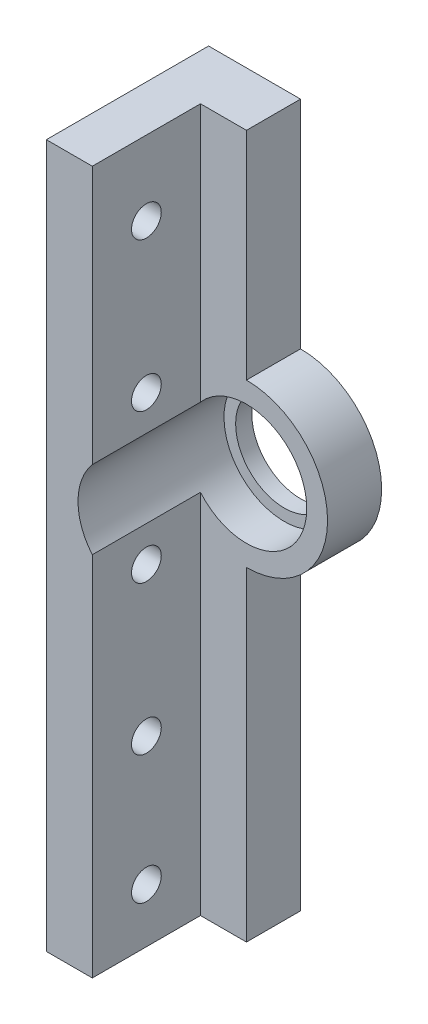
SolidWorks part; units mm, degrees
ref_plane "Front Plane" through (0, 0, 0) normal (0, 0, 1) x (1, 0, 0)
ref_plane "Top Plane" through (0, 0, 0) normal (0, 1, 0) x (1, 0, 0)
ref_plane "Right Plane" through (0, 0, 0) normal (1, 0, 0) x (0, 0, -1)
sketch "Sketch4" plane through (0, 0, -7) normal (0, 0, -1) x (-1, 0, 0)
  line L5 (0, 55) -> (0, 15)
  line L6 (17, 55) -> (0, 55)
  line L7 (17, -75) -> (17, 55)
  line L8 (0, -75) -> (17, -75)
  line L9 (0, -15) -> (0, -75)
  line L10 (0, 55) -> (0, 15)
  line L11 (17, 55) -> (0, 55)
  line L12 (17, -75) -> (17, 55)
  line L14 (0, -15) -> (0, -75)
  line L20 (0, -75) -> (17, -75)
  circle A0 centre (0, 0) radius 9 construction
  arc A1 (0, 15) -> (0, -15) centre (0, 0) ccw
  arc A2 (0, 15) -> (0, -15) centre (0, 0) ccw
  circle A3 centre (0, 0) radius 9
  dimension "D1" = 0
extrude "Boss-Extrude1" add sketch "Sketch4" along normal blind 3
sketch "Sketch5" plane through (0, 0, -7) normal (0, 0, 1) x (1, 0, 0)
  line L2 (0, -11.15) -> (0, -15)
  line L3 (0, 11.15) -> (0, 55)
  line L4 (-7, 55) -> (-7, 8.6789)
  line L5 (0, 55) -> (-7, 55)
  line L6 (0, 11.15) -> (0, 55)
  line L7 (-7, 55) -> (-7, 8.6789)
  line L8 (0, 55) -> (-7, 55)
  line L9 (0, 15) -> (0, 11.15)
  line L10 (0, -11.15) -> (0, -15)
  line L11 (0, 15) -> (0, 11.15)
  line L13 (0, -75) -> (0, -11.15)
  line L14 (-7, -75) -> (0, -75)
  line L15 (-7, -8.6789) -> (-7, -75)
  line L16 (0, -75) -> (0, -11.15)
  line L18 (-7, -8.6789) -> (-7, -75)
  line L21 (0, -55) -> (0, -15)
  line L22 (-17, -55) -> (0, -55)
  line L23 (-17, 55) -> (-17, -55)
  line L24 (0, 55) -> (-17, 55)
  line L25 (0, 15) -> (0, 55)
  line L26 (0, -55) -> (0, -15)
  line L27 (-17, -55) -> (0, -55)
  line L28 (-17, 55) -> (-17, -55)
  line L29 (0, 55) -> (-17, 55)
  line L30 (0, 15) -> (0, 55)
  line L37 (-7, -75) -> (0, -75)
  circle A0 centre (0, 0) radius 11.15
  arc A1 (0, 11.15) -> (-7, 8.6789) centre (0, 0) ccw
  arc A2 (0, 11.15) -> (-7, 8.6789) centre (0, 0) ccw
  arc A3 (-7, -8.6789) -> (0, -11.15) centre (0, 0) ccw
  arc A4 (0, -11.15) -> (0, 11.15) centre (0, 0) ccw
  arc A5 (0, -15) -> (0, 15) centre (0, 0) ccw
  arc A6 (0, -11.15) -> (0, 11.15) centre (0, 0) ccw
  arc A7 (0, -15) -> (0, 15) centre (0, 0) ccw
  arc A8 (-7, -8.6789) -> (0, -11.15) centre (0, 0) ccw
  arc A9 (0, -15) -> (0, 15) centre (0, 0) ccw
  arc A10 (0, -15) -> (0, 15) centre (0, 0) ccw
  dimension "D1" = 0
  dimension "D2" = 0
  dimension "D3" = 0
  dimension "D4" = 0
extrude "Boss-Extrude3" add sketch "Sketch5" along normal blind 7
sketch "Sketch6" plane through (0, 0, 0) normal (0, 0, 1) x (1, 0, 0)
  line L0 (0, 15) -> (0, -15)
  line L1 (-8.5, 55) -> (-8.5, 15)
  line L2 (0, 55) -> (-17, 55) construction
  line L3 (-8.5, 15) -> (0, 15)
  line L4 (0, -15) -> (-8.5, -15)
  line L5 (-8.5, -15) -> (-8.5, -55)
  line L7 (-8.5, 15) -> (-8.5, -16.0739)
  line L12 (0, 15) -> (0, 55)
  line L13 (0, 55) -> (-17, 55)
  line L14 (-17, 55) -> (-17, -55)
  line L15 (-17, -55) -> (0, -55)
  line L16 (0, -55) -> (0, -15)
  line L17 (0, 15) -> (0, 55)
  line L18 (0, 55) -> (-17, 55)
  line L19 (-17, 55) -> (-17, -55)
  line L21 (0, -55) -> (0, -15)
  line L23 (-17, -55) -> (0, -55)
  circle A0 centre (0, 0) radius 11.15
  arc A1 (0, -15) -> (0, 15) centre (0, 0) ccw construction
  arc A3 (0, -15) -> (0, 15) centre (0, 0) ccw
  arc A4 (0, -15) -> (0, 15) centre (0, 0) ccw
  dimension "D1" = 0
extrude "Boss-Extrude4" add sketch "Sketch6" along normal blind 10
sketch "Sketch7" plane through (0, 0, 10) normal (0, 0, 1) x (1, 0, 0)
  line L5 (-8.5, 7.2161) -> (-8.5, 55)
  line L6 (-8.5, 55) -> (-17, 55)
  line L7 (-17, 55) -> (-17, -55)
  line L8 (-17, -55) -> (-8.5, -55)
  line L9 (-8.5, -55) -> (-8.5, -7.2161)
  line L10 (-8.5, 7.2161) -> (-8.5, 55)
  line L11 (-8.5, 55) -> (-17, 55)
  line L12 (-17, 55) -> (-17, -55)
  line L14 (-8.5, -55) -> (-8.5, -7.2161)
  line L15 (-17, -55) -> (-8.5, -55)
  arc A1 (-8.5, 7.2161) -> (-8.5, -7.2161) centre (0, 0) ccw
  arc A2 (-8.5, 7.2161) -> (-8.5, -7.2161) centre (0, 0) ccw
  dimension "D1" = 0
extrude "Boss-Extrude5" add sketch "Sketch7" along normal blind 10
sketch "Sketch8" plane through (-8.5, 0, 0) normal (1, 0, 0) x (0, 0, -1)
  line L0 (-20, 0) -> (0, 0)
  line L3 (-20, 7.2161) -> (-20, -7.2161) construction
  line L4 (-10, 55) -> (-10, 27.5)
  line L5 (-20, 55) -> (0, 55) construction
  line L6 (-10, 27.5) -> (0, 27.5)
  line L7 (0, 15) -> (0, 55) construction
  circle A0 centre (-10, 41.25) radius 2.75
  circle A1 centre (-10, 13.75) radius 2.75
  circle A2 centre (-10, -13.75) radius 2.75
  circle A3 centre (-10, -41.25) radius 2.75
  dimension "D1" = 5.5
extrude "Cut-Extrude2" cut sketch "Sketch8" against normal blind 10 contours L4 A0 | A1 | L4 A0 | A2 | A3
sketch "Sketch10" plane through (0, 0, -7) normal (0, 0, 1) x (1, 0, 0)
  line L4 (0, -55) -> (-17, -55)
  line L5 (-17, -55) -> (-17, -75)
  line L6 (-17, -75) -> (0, -75)
  line L7 (0, -75) -> (0, -55)
  line L8 (0, -55) -> (-17, -55)
  line L9 (-17, -55) -> (-17, -75)
  line L10 (-17, -75) -> (0, -75)
  line L11 (0, -75) -> (0, -55)
  dimension "D1" = 0
extrude "Boss-Extrude7" add sketch "Sketch10" along normal up to surface (7 mm away) up to face at (0.0813, 0, 0)
sketch "Sketch11" plane through (0, -55, 0) normal (0, -1, 0) x (1, 0, 0)
  line L4 (-17, 20) -> (-17, 0)
  line L5 (-17, 0) -> (-8.5, 0)
  line L6 (-8.5, 0) -> (-8.5, 20)
  line L7 (-8.5, 20) -> (-17, 20)
  line L8 (-17, 20) -> (-17, 0)
  line L9 (-17, 0) -> (-8.5, 0)
  line L10 (-8.5, 0) -> (-8.5, 20)
  line L11 (-8.5, 20) -> (-17, 20)
  dimension "D1" = 0
extrude "Boss-Extrude8" add sketch "Sketch11" along normal up to surface (20 mm away) up to face at (-8.5, -75, -5)
sketch "Sketch12" plane through (-8.5, 0, 0) normal (1, 0, 0) x (0, 0, -1)
  line L0 (-10, -65) -> (-10, -75)
  line L1 (-20, -75) -> (0, -75) construction
  circle A0 centre (-10, -65) radius 2.75
  dimension "D1" = 5.5
extrude "Cut-Extrude3" cut sketch "Sketch12" against normal blind 20
